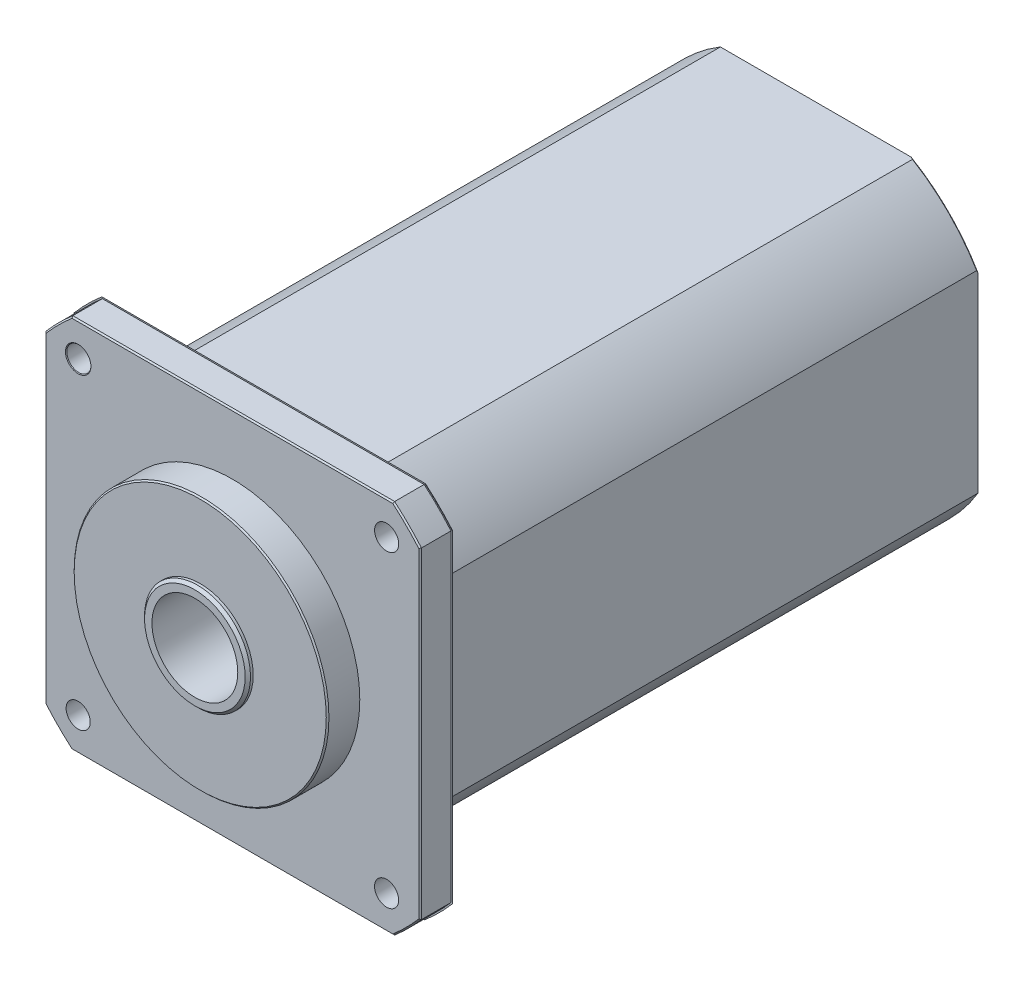
SolidWorks part; units mm, degrees
ref_plane "Front Plane" through (0, 0, 0) normal (0, 0, 1) x (1, 0, 0)
ref_plane "Top Plane" through (0, 0, 0) normal (0, 1, 0) x (1, 0, 0)
ref_plane "Right Plane" through (0, 0, 0) normal (1, 0, 0) x (0, 0, -1)
ref_plane "Plane3" through (0, 0, 15.25) normal (0, 0, -1) x (-1, 0, 0)
sketch "Sketch17" plane through (0, 0, 15.25) normal (0, 0, -1) x (-1, 0, 0)
  line L0 (-68.7585, -77.5599) -> (51.2415, -77.5599)
  line L1 (61.2415, -67.5599) -> (61.2415, 52.4401)
  line L2 (51.2415, 62.4401) -> (-68.7585, 62.4401)
  line L3 (-78.7585, 52.4401) -> (-78.7585, -67.5599)
  arc A0 (51.2415, -77.5599) -> (61.2415, -67.5599) centre (-8.7585, -7.5599) ccw
  arc A1 (61.2415, 52.4401) -> (51.2415, 62.4401) centre (-8.7585, -7.5599) ccw
  arc A2 (-68.7585, 62.4401) -> (-78.7585, 52.4401) centre (-8.7585, -7.5599) ccw
  arc A3 (-78.7585, -67.5599) -> (-68.7585, -77.5599) centre (-8.7585, -7.5599) ccw
  point P11 (-8.7585, -7.5599)
  dimension "D1" = 70
  dimension "D2" = 70
  dimension "D3" = 70
  dimension "D4" = 70
  dimension "D5" = 10
extrude "Boss-Extrude10" add sketch "Sketch17" against normal blind 0.5 draft 45 separate body draft outward yes
sketch "Sketch18" plane through (0, 0, 15.75) normal (0, 0, 1) x (1, 0, 0)
  line L0 (-51.2415, 62.4401) -> (68.7585, 62.4401)
  line L1 (78.7585, 52.4401) -> (78.7585, -67.5599)
  line L2 (68.7585, -77.5599) -> (-51.2415, -77.5599)
  line L3 (-61.2415, -67.5599) -> (-61.2415, 52.4401)
  arc A0 (-61.2415, 52.4401) -> (-51.2415, 62.4401) centre (8.7585, -7.5599) cw
  arc A1 (68.7585, 62.4401) -> (78.7585, 52.4401) centre (8.7585, -7.5599) cw
  arc A2 (78.7585, -67.5599) -> (68.7585, -77.5599) centre (8.7585, -7.5599) cw
  arc A3 (-51.2415, -77.5599) -> (-61.2415, -67.5599) centre (8.7585, -7.5599) cw
  point P10 (8.7585, -7.5599)
  dimension "D1" = 70
  dimension "D2" = 70
  dimension "D3" = 70
  dimension "D4" = 70
  dimension "D5" = 10
extrude "Boss-Extrude11" add sketch "Sketch18" along normal blind 11.5
sketch "Sketch19" plane through (0, 0, 27.25) normal (0, 0, 1) x (1, 0, 0)
  circle A0 centre (8.7585, -7.5599) radius 47.5
  point P3 (8.7585, -7.5599)
  dimension "D1" = 95
extrude "Boss-Extrude12" add sketch "Sketch19" along normal blind 12
sketch "Sketch20" plane through (0, 0, 39.25) normal (0, 0, 1) x (1, 0, 0)
  circle A0 centre (8.7585, -7.5599) radius 19.75
extrude "Boss-Extrude13" add sketch "Sketch20" along normal blind 1
sketch "Sketch21" plane through (0, 0, 40.25) normal (0, 0, 1) x (1, 0, 0)
  circle A0 centre (8.7585, -7.5599) radius 19.75
extrude "Boss-Extrude14" add sketch "Sketch21" along normal blind 1 draft 45
sketch "Sketch22" plane through (0, 0, 41.25) normal (0, 0, 1) x (1, 0, 0)
  circle A0 centre (8.7585, -7.5599) radius 16
extrude "Boss-Extrude15" add sketch "Sketch22" along normal blind 50
ref_plane "Plane4" through (0, 11.4401, 0) normal (0, 1, 0) x (1, 0, 0)
sketch "Sketch28" plane through (0, 0, 15.25) normal (0, 0, -1) x (-1, 0, 0)
  circle A0 centre (-8.7585, -7.5599) radius 57
extrude "Boss-Extrude17" add sketch "Sketch28" along normal blind 0.5 draft 45 draft outward yes
sketch "Sketch29" plane through (0, 0, 14.75) normal (0, 0, -1) x (-1, 0, 0)
  line L5 (-73.9505, -72.7519) -> (56.4336, 57.6321) construction
  line L6 (-73.9505, 57.6321) -> (56.4336, -72.7519) construction
  line L7 (-44.814, -67.5599) -> (27.2971, -67.5599)
  line L8 (-68.7585, -43.6154) -> (-68.7585, 28.4956)
  line L9 (-44.814, 52.4401) -> (27.2971, 52.4401)
  line L10 (51.2415, -43.6154) -> (51.2415, 28.4956)
  line L11 (-68.7585, -67.5599) -> (51.2415, 52.4401) construction
  line L12 (-68.7585, 52.4401) -> (51.2415, -67.5599) construction
  arc A0 (-44.814, 52.4401) -> (-68.7585, 28.4956) centre (-8.7585, -7.5599) ccw
  arc A1 (61.2415, 52.4401) -> (51.2415, 62.4401) centre (-8.7585, -7.5599) ccw construction
  arc A2 (-68.7585, -43.6154) -> (-44.814, -67.5599) centre (-8.7585, -7.5599) ccw
  arc A3 (27.2971, -67.5599) -> (51.2415, -43.6154) centre (-8.7585, -7.5599) ccw
  arc A4 (51.2415, 28.4956) -> (27.2971, 52.4401) centre (-8.7585, -7.5599) ccw
  point P3 (-8.7585, -7.5599)
  dimension "D1" = 140
  dimension "D2" = 120
extrude "Boss-Extrude18" add sketch "Sketch29" along normal blind 205.5
hole_wizard "Ø9.0 (9) Diameter Hole2" positions "Sketch31" profile "Sketch30" hole size "Ø9.0" standard "ANSI Metric" end condition through all
sketch "Sketch31" plane through (0, 0, 15.25) normal (0, 0, -1) x (-1, 0, 0)
  line L0 (-8.7585, -7.5599) -> (-8.7585, 4.8965) construction
  line L2 (-8.7585, -7.5599) -> (-8.7585, -18.0122) construction
  line L4 (-8.7585, -7.5599) -> (-8.7585, -18.0122) construction
  line L6 (-26.5233, -7.5599) -> (6.5358, -7.5599) construction
  point P0 (48.7415, 49.9401)
  point P1 (-66.2585, 49.9401)
  point P2 (-66.2585, -65.0599)
  point P3 (48.7415, -65.0599)
  dimension "D1" = 57.5
  dimension "D2" = 57.5
  dimension "D3" = 57.5
  dimension "D4" = 57.5
  dimension "D5" = 57.5
  dimension "D6" = 57.5
  dimension "D7" = 57.5
  dimension "D8" = 57.5
sketch "Sketch30" plane through (-48.7415, 49.9401, 15.25) normal (1, 0, 0) x (0, 1, 0)
  line L0 (0, 0) -> (0, 76)
  line L1 (0, 76) -> (4.5, 76)
  line L2 (4.5, 76) -> (4.5, 0)
  line L5 (4.5, 0) -> (0, 0)
  line L11 (0, -6.35) -> (0, 107.95) construction
  dimension "Thru Hole Dia." = 9
  dimension "Thru Hole Depth" = 76
chamfer "Chamfer5" distance 0.5 angle 45 11 edges at (58.2559, 41.9375, -190.75) (-53.2415, 49.9401, 15.25) (73.9505, -72.7519, 27.25) (8.7585, -77.5599, 27.25) (78.7585, -7.5599, 27.25) (-56.4336, -72.7519, 27.25) (73.9505, 57.6321, 27.25) (-61.2415, -7.5599, 27.25) (8.7585, 62.4401, 27.25) (-56.4336, 57.6321, 27.25) (56.2585, -7.5599, 39.25)
chamfer "Chamfer6" distance 0.25 angle 45 1 edges at (-53.2415, 49.9401, 27.25)
ref_plane "Plane5" through (0, 0, 99.25) normal (0, 0, 1) x (1, 0, 0)
sketch "Sketch32" plane through (0, 0, 99.25) normal (0, 0, 1) x (1, 0, 0)
  circle A0 centre (8.7585, -7.5599) radius 16
extrude "Cut-Extrude1" cut sketch "Sketch32" against normal through all
